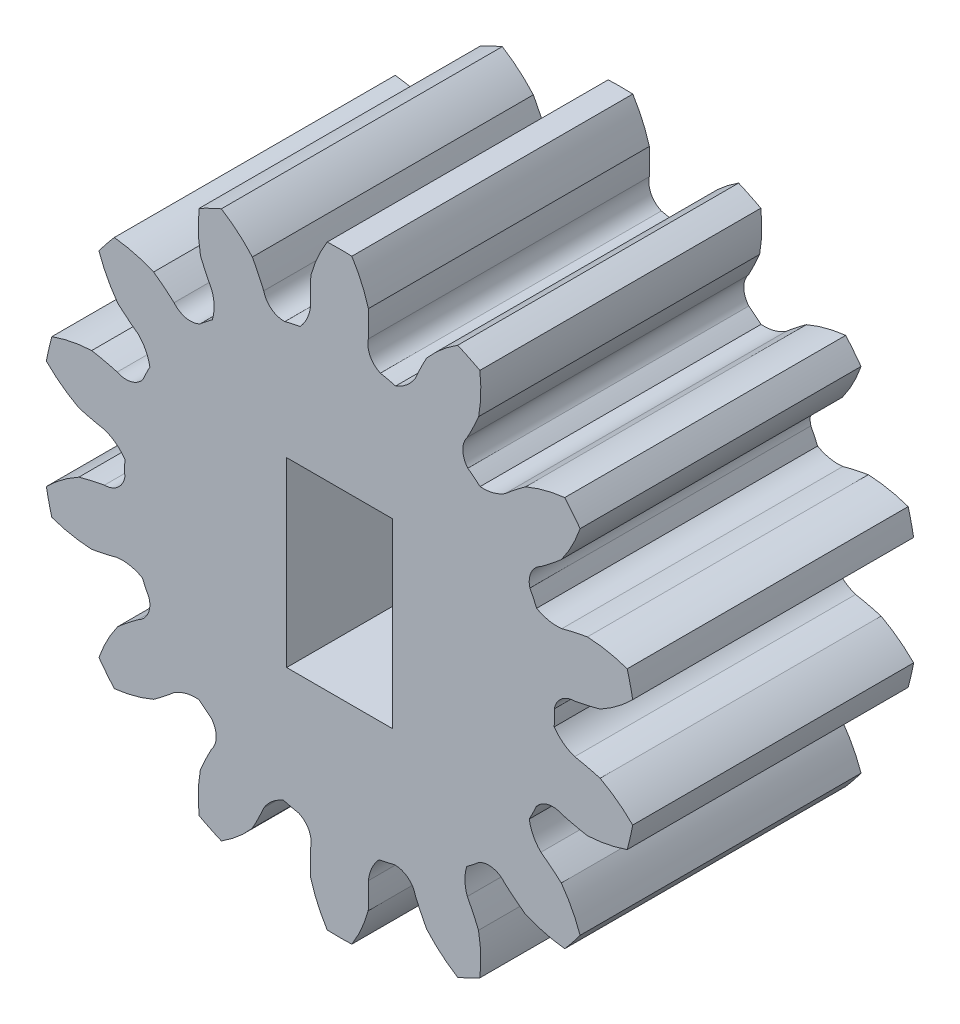
SolidWorks part; units mm, degrees
ref_plane "Front Plane" through (0, 0, 0) normal (0, 0, 1) x (1, 0, 0)
ref_plane "Top Plane" through (0, 0, 0) normal (0, 1, 0) x (1, 0, 0)
ref_plane "Right Plane" through (0, 0, 0) normal (1, 0, 0) x (0, 0, -1)
ref_plane "Plane1" through (0, 0, 20) normal (0, 0, 1) x (1, 0, 0)
ref_plane "Plane2" through (0, 0, 28.5) normal (0, 0, 1) x (1, 0, 0)
sketch "Sketch1" plane through (0, 0, 20) normal (0, 0, 1) x (1, 0, 0)
  circle A1 centre (0, 20.9252) radius 6.5
  dimension "D1" = 13
sketch "Sketch2" plane through (0, 0, 20) normal (0, 0, 1) x (1, 0, 0)
  arc A0 (-0.3724, 29.9378) -> (0.3724, 29.9378) centre (0, 20.8103) cw
  arc A1 (0.3724, 29.9378) -> (0.873, 28.8151) centre (-3.1544, 27.6923) cw
  arc A2 (0.873, 28.8151) -> (0.873, 28.0231) centre (-7.7307, 28.4191) cw
  arc A3 (0.873, 28.0231) -> (1.2364, 27.3066) centre (1.4883, 27.8847) ccw
  circle A4 centre (0, 20.9252) radius 6.5 construction
  arc A5 (-0.873, 28.0231) -> (-1.1929, 27.3148) centre (-2.1071, 28.1541) cw
  arc A6 (-0.868, 28.8151) -> (-0.873, 28.0231) centre (7.003, 28.369) ccw
  arc A7 (-0.3724, 29.9378) -> (-0.868, 28.8151) centre (3.1633, 27.7064) ccw
  arc A8 (-1.1929, 27.3148) -> (1.2364, 27.3066) centre (0, 20.9252) cw
  arc A9 (1.6976, 27.1996) -> (3.8827, 26.1381) centre (0, 20.9252) cw
  arc A10 (3.8662, 26.9414) -> (3.8827, 26.1381) centre (4.3605, 26.5498) ccw
  arc A11 (4.2099, 27.655) -> (3.8662, 26.9414) centre (-3.7136, 31.0312) cw
  arc A12 (4.246, 28.8837) -> (4.2099, 27.655) centre (0.0942, 28.3908) cw
  arc A13 (3.5748, 29.2069) -> (4.246, 28.8837) centre (-0.0499, 20.8217) cw
  arc A14 (3.5748, 29.2069) -> (2.6413, 28.4104) centre (5.7923, 25.6624) ccw
  arc A15 (2.6413, 28.4104) -> (2.2931, 27.699) centre (9.5392, 24.5934) ccw
  arc A16 (2.2931, 27.699) -> (1.6976, 27.1996) centre (1.238, 28.3525) cw
  arc A17 (4.2518, 25.8417) -> (5.76, 23.9372) centre (0, 20.9252) cw
  arc A18 (6.0937, 24.6682) -> (5.76, 23.9372) centre (6.3691, 24.1008) ccw
  arc A19 (6.7129, 25.162) -> (6.0937, 24.6682) centre (1.039, 31.6417) cw
  arc A20 (7.2785, 26.2533) -> (6.7129, 25.162) centre (3.324, 27.6106) cw
  arc A21 (6.8141, 26.8357) -> (7.2785, 26.2533) centre (-0.0899, 20.8536) cw
  arc A22 (6.8141, 26.8357) -> (5.6274, 26.5231) centre (7.2741, 22.6801) ccw
  arc A23 (5.6274, 26.5231) -> (5.005, 26.0332) centre (10.1861, 20.0912) ccw
  arc A24 (5.005, 26.0332) -> (4.2518, 25.8417) centre (4.338, 27.0798) cw
  arc A25 (5.964, 23.51) -> (6.4965, 21.1398) centre (0, 20.9252) cw
  arc A26 (7.1142, 21.6535) -> (6.4965, 21.1398) centre (7.1162, 21.0229) ccw
  arc A27 (7.8864, 21.8298) -> (7.1142, 21.6535) centre (5.5858, 30.1296) cw
  arc A28 (8.8695, 22.5676) -> (7.8864, 21.8298) centre (5.8955, 25.5063) cw
  arc A29 (8.7037, 23.2938) -> (8.8695, 22.5676) centre (-0.112, 20.8997) cw
  arc A30 (8.7037, 23.2938) -> (7.499, 23.5271) centre (7.3151, 19.3502) ccw
  arc A31 (7.499, 23.5271) -> (6.7257, 23.3558) centre (8.8155, 15.7542) ccw
  arc A32 (6.7257, 23.3558) -> (5.964, 23.51) centre (6.5788, 24.5881) cw
  arc A33 (6.4948, 20.6664) -> (5.9462, 18.2998) centre (0, 20.9252) cw
  arc A34 (6.7257, 18.4947) -> (5.9462, 18.2998) centre (6.4538, 17.9257) ccw
  arc A35 (7.4978, 18.3184) -> (6.7257, 18.4947) centre (9.0263, 26.7945) cw
  arc A36 (8.7037, 18.5567) -> (7.4978, 18.3184) centre (7.2993, 22.4947) cw
  arc A37 (8.8695, 19.2829) -> (8.7037, 18.5567) centre (-0.112, 20.9508) cw
  arc A38 (8.8695, 19.2829) -> (7.8852, 20.0158) centre (5.9073, 16.3323) ccw
  arc A39 (7.8852, 20.0158) -> (7.1142, 20.1969) centre (5.6988, 12.4414) ccw
  arc A40 (7.1142, 20.1969) -> (6.4948, 20.6664) centre (7.5165, 21.371) cw
  arc A41 (5.7394, 17.874) -> (4.2182, 15.9799) centre (0, 20.9252) cw
  arc A42 (5.005, 15.8172) -> (4.2182, 15.9799) centre (4.5132, 15.4225) ccw
  arc A43 (5.6243, 15.3234) -> (5.005, 15.8172) centre (10.679, 22.297) cw
  arc A44 (6.8141, 15.0148) -> (5.6243, 15.3234) centre (7.2574, 19.1722) cw
  arc A45 (7.2785, 15.5972) -> (6.8141, 15.0148) centre (-0.0899, 20.9969) cw
  arc A46 (7.2785, 15.5972) -> (6.7098, 16.6846) centre (3.3295, 14.224) ccw
  arc A47 (6.7098, 16.6846) -> (6.0937, 17.1823) centre (1.4535, 10.8089) ccw
  arc A48 (6.0937, 17.1823) -> (5.7394, 17.874) centre (6.9655, 18.0655) cw
  arc A49 (3.8471, 15.686) -> (1.6548, 14.6394) centre (0, 20.9252) cw
  arc A50 (2.2931, 14.1515) -> (1.6548, 14.6394) centre (1.6787, 14.0092) ccw
  arc A51 (2.6367, 13.4379) -> (2.2931, 14.1515) centre (10.2166, 17.5277) cw
  arc A52 (3.5748, 12.6436) -> (2.6367, 13.4379) centre (5.7781, 16.1969) cw
  arc A53 (4.246, 12.9668) -> (3.5748, 12.6436) centre (-0.0499, 21.0288) cw
  arc A54 (4.246, 12.9668) -> (4.2053, 14.1933) centre (0.0922, 13.4431) ccw
  arc A55 (4.2053, 14.1933) -> (3.8662, 14.909) centre (-3.0798, 11.1801) ccw
  arc A56 (3.8662, 14.909) -> (3.8471, 15.686) centre (5.035, 15.3265) cw
  arc A57 (1.1929, 14.5356) -> (-1.2364, 14.5439) centre (0, 20.9252) cw
  arc A58 (-0.873, 13.8273) -> (-1.2364, 14.5439) centre (-1.4883, 13.9658) ccw
  arc A59 (-0.873, 13.0353) -> (-0.873, 13.8273) centre (7.7307, 13.4313) cw
  arc A60 (-0.3724, 11.9127) -> (-0.873, 13.0353) centre (3.1544, 14.1581) cw
  arc A61 (0.3724, 11.9127) -> (-0.3724, 11.9127) centre (0, 21.0402) cw
  arc A62 (0.3724, 11.9127) -> (0.868, 13.0353) centre (-3.1633, 14.144) ccw
  arc A63 (0.868, 13.0353) -> (0.873, 13.8273) centre (-7.003, 13.4814) ccw
  arc A64 (0.873, 13.8273) -> (1.1929, 14.5356) centre (2.1071, 13.6964) cw
  arc A65 (-1.6976, 14.6508) -> (-3.8827, 15.7123) centre (0, 20.9252) cw
  arc A66 (-3.8662, 14.909) -> (-3.8827, 15.7123) centre (-4.3605, 15.3007) ccw
  arc A67 (-4.2099, 14.1955) -> (-3.8662, 14.909) centre (3.7136, 10.8192) cw
  arc A68 (-4.246, 12.9668) -> (-4.2099, 14.1955) centre (-0.0942, 13.4597) cw
  arc A69 (-3.5748, 12.6436) -> (-4.246, 12.9668) centre (0.0499, 21.0288) cw
  arc A70 (-3.5748, 12.6436) -> (-2.6413, 13.4401) centre (-5.7923, 16.1881) ccw
  arc A71 (-2.6413, 13.4401) -> (-2.2931, 14.1515) centre (-9.5392, 17.2571) ccw
  arc A72 (-2.2931, 14.1515) -> (-1.6976, 14.6508) centre (-1.238, 13.498) cw
  arc A73 (-4.2518, 16.0087) -> (-5.76, 17.9132) centre (0, 20.9252) cw
  arc A74 (-6.0937, 17.1823) -> (-5.76, 17.9132) centre (-6.3691, 17.7496) ccw
  arc A75 (-6.7129, 16.6885) -> (-6.0937, 17.1823) centre (-1.039, 10.2088) cw
  arc A76 (-7.2785, 15.5972) -> (-6.7129, 16.6885) centre (-3.324, 14.2398) cw
  arc A77 (-6.8141, 15.0148) -> (-7.2785, 15.5972) centre (0.0899, 20.9969) cw
  arc A78 (-6.8141, 15.0148) -> (-5.6274, 15.3274) centre (-7.2741, 19.1704) ccw
  arc A79 (-5.6274, 15.3274) -> (-5.005, 15.8172) centre (-10.1861, 21.7593) ccw
  arc A80 (-5.005, 15.8172) -> (-4.2518, 16.0087) centre (-4.338, 14.7707) cw
  arc A81 (-5.964, 18.3404) -> (-6.4965, 20.7107) centre (0, 20.9252) cw
  arc A82 (-7.1142, 20.1969) -> (-6.4965, 20.7107) centre (-7.1162, 20.8276) ccw
  arc A83 (-7.8864, 20.0207) -> (-7.1142, 20.1969) centre (-5.5858, 11.7208) cw
  arc A84 (-8.8695, 19.2829) -> (-7.8864, 20.0207) centre (-5.8955, 16.3441) cw
  arc A85 (-8.7037, 18.5567) -> (-8.8695, 19.2829) centre (0.112, 20.9508) cw
  arc A86 (-8.7037, 18.5567) -> (-7.499, 18.3234) centre (-7.3151, 22.5003) ccw
  arc A87 (-7.499, 18.3234) -> (-6.7257, 18.4947) centre (-8.8155, 26.0963) ccw
  arc A88 (-6.7257, 18.4947) -> (-5.964, 18.3404) centre (-6.5788, 17.2624) cw
  arc A89 (-6.4948, 21.1841) -> (-5.9462, 23.5506) centre (0, 20.9252) cw
  arc A90 (-6.7257, 23.3558) -> (-5.9462, 23.5506) centre (-6.4538, 23.9248) ccw
  arc A91 (-7.4978, 23.532) -> (-6.7257, 23.3558) centre (-9.0263, 15.0559) cw
  arc A92 (-8.7037, 23.2938) -> (-7.4978, 23.532) centre (-7.2993, 19.3558) cw
  arc A93 (-8.8695, 22.5676) -> (-8.7037, 23.2938) centre (0.112, 20.8997) cw
  arc A94 (-8.8695, 22.5676) -> (-7.8852, 21.8347) centre (-5.9073, 25.5182) ccw
  arc A95 (-7.8852, 21.8347) -> (-7.1142, 21.6535) centre (-5.6988, 29.4091) ccw
  arc A96 (-7.1142, 21.6535) -> (-6.4948, 21.1841) centre (-7.5165, 20.4795) cw
  arc A97 (-5.7394, 23.9764) -> (-4.2182, 25.8706) centre (0, 20.9252) cw
  arc A98 (-5.005, 26.0332) -> (-4.2182, 25.8706) centre (-4.5132, 26.428) ccw
  arc A99 (-5.6243, 26.5271) -> (-5.005, 26.0332) centre (-10.679, 19.5535) cw
  arc A100 (-6.8141, 26.8357) -> (-5.6243, 26.5271) centre (-7.2574, 22.6783) cw
  arc A101 (-7.2785, 26.2533) -> (-6.8141, 26.8357) centre (0.0899, 20.8536) cw
  arc A102 (-7.2785, 26.2533) -> (-6.7098, 25.1659) centre (-3.3295, 27.6264) ccw
  arc A103 (-6.7098, 25.1659) -> (-6.0937, 24.6682) centre (-1.4535, 31.0415) ccw
  arc A104 (-6.0937, 24.6682) -> (-5.7394, 23.9764) centre (-6.9655, 23.7849) cw
  arc A105 (-3.8471, 26.1645) -> (-1.6548, 27.2111) centre (0, 20.9252) cw
  arc A106 (-2.2931, 27.699) -> (-1.6548, 27.2111) centre (-1.6787, 27.8412) ccw
  arc A107 (-2.6367, 28.4126) -> (-2.2931, 27.699) centre (-10.2166, 24.3228) cw
  arc A108 (-3.5748, 29.2069) -> (-2.6367, 28.4126) centre (-5.7781, 25.6535) cw
  arc A109 (-4.246, 28.8837) -> (-3.5748, 29.2069) centre (0.0499, 20.8217) cw
  arc A110 (-4.246, 28.8837) -> (-4.2053, 27.6572) centre (-0.0922, 28.4074) ccw
  arc A111 (-4.2053, 27.6572) -> (-3.8662, 26.9414) centre (3.0798, 30.6704) ccw
  arc A112 (-3.8662, 26.9414) -> (-3.8471, 26.1645) centre (-5.035, 26.524) cw
  point P192 (0, 20.9252)
  dimension "D1" = 14
extrude "Boss-Extrude1" add sketch "Sketch2" along normal blind 8.5
sketch "Sketch3" plane through (0, 0, 28.5) normal (0, 0, 1) x (1, 0, 0)
  line L0 (-3.9726, 20.9252) -> (15.3734, 20.9252) construction
  line L1 (0, 24.8978) -> (0, 8.7425) construction
  line L3 (-1.6, 23.6752) -> (1.6, 23.6752)
  line L4 (-1.6, 23.6752) -> (-1.6, 18.1752)
  line L5 (-1.6, 18.1752) -> (1.6, 18.1752)
  line L6 (1.6, 23.6752) -> (1.6, 18.1752)
  dimension "D1" = 3.2
  dimension "D2" = 5.5
  dimension "D3" = 1.6
  dimension "D4" = 2.75
extrude "Boss-Extrude2" add sketch "Sketch1" along normal blind 8.5
extrude "Cut-Extrude1" cut sketch "Sketch3" against normal blind 6
